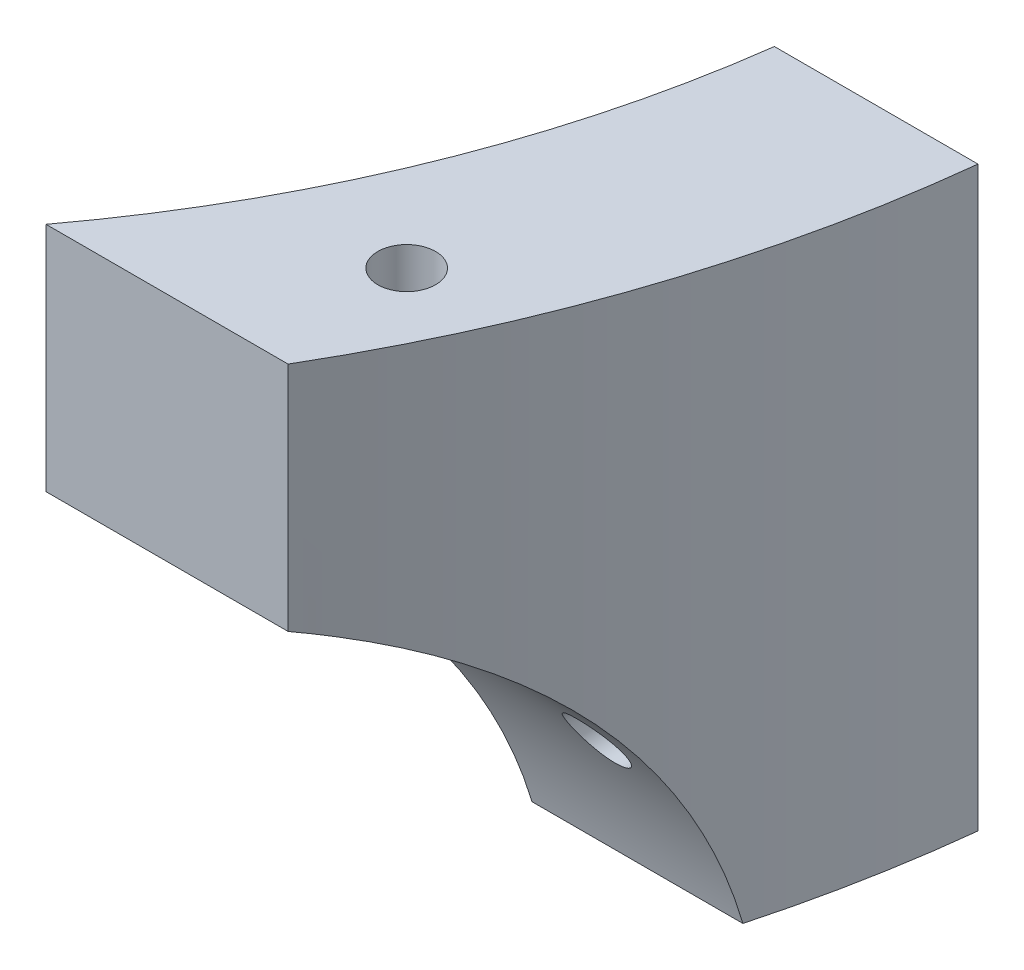
SolidWorks part; units mm, degrees
material "1023 Carbon Steel Sheet (SS)"
ref_plane "Front Plane" through (0, 0, 0) normal (0, 0, 1) x (1, 0, 0)
ref_plane "Top Plane" through (0, 0, 0) normal (0, 1, 0) x (1, 0, 0)
ref_plane "Right Plane" through (0, 0, 0) normal (1, 0, 0) x (0, 0, -1)
sketch "Sketch1" plane through (0, 0, 0) normal (0, 1, 0) x (1, 0, 0)
  line L0 (-1000, 0) -> (-104.805, 0) construction
  line L1 (0, -1000) -> (0, 49000) construction
  line L2 (91.805, -10) -> (90.2527, -10)
  line L3 (-76.805, 0) -> (76.805, 0)
  line L7 (-91.805, -10) -> (-90.2527, -10)
  line L9 (104.805, 0) -> (49000, 0) construction
  line L10 (-76.805, 0) -> (-76.805, 20)
  line L12 (-76.805, 0) -> (76.805, 0) construction
  line L13 (91.805, 20) -> (91.805, -10)
  line L14 (76.805, 20) -> (91.805, 20)
  line L17 (-76.805, 20) -> (-91.805, 20)
  line L18 (76.805, 0) -> (76.805, 20)
  line L19 (-91.805, 20) -> (-91.805, -10)
  arc A0 (-90.2527, -10) -> (90.2527, -10) centre (0, 0) ccw
  arc A1 (-76.805, 0) -> (76.805, 0) centre (0, 0) ccw
  dimension "D1" = 181.61
  dimension "D2" = 14
  dimension "D3" = 30
  dimension "D4" = 15
extrude "Boss-Extrude1" add sketch "Sketch1" against normal blind 60
sketch "Sketch25" plane through (0, -60, 0) normal (0, -1, 0) x (-1, 0, 0)
  line L0 (76.805, 20) -> (91.805, -10)
  line L1 (91.805, -10) -> (76.805, -10)
  line L2 (76.805, -10) -> (91.805, 20)
  line L3 (-91.805, -10) -> (-76.805, 20)
  line L4 (81.555, -3.5) -> (87.055, -3.5)
  line L5 (81.555, -3.5) -> (81.555, 13.5)
  line L6 (81.555, 13.5) -> (87.055, 13.5)
  line L7 (87.055, -3.5) -> (87.055, 13.5)
  line L8 (81.555, -3.5) -> (87.055, 13.5) construction
  line L9 (81.555, 13.5) -> (87.055, -3.5) construction
  line L10 (-76.805, 20) -> (-77.8097, -10)
  line L11 (-77.8097, -10) -> (-91.805, -10)
  line L12 (-77.8097, -10) -> (-91.805, 20)
  line L14 (-87.055, -3.5) -> (-81.555, -3.5)
  line L15 (-87.055, -3.5) -> (-87.055, 13.5)
  line L16 (-87.055, 13.5) -> (-81.555, 13.5)
  line L17 (-81.555, -3.5) -> (-81.555, 13.5)
  line L18 (-87.055, -3.5) -> (-81.555, 13.5) construction
  line L19 (-87.055, 13.5) -> (-81.555, -3.5) construction
  point P4 (84.305, 5)
  point P16 (-84.305, 5)
  dimension "D1" = 5.5
  dimension "D2" = 17
  dimension "D3" = 17
  dimension "D4" = 5.5
extrude "Boss-Extrude3" add sketch "Sketch25" along normal blind 20 contours L15 L16 L17 L14 | L5 L6 L7 L4
ref_plane "Plane4" through (0, 0, 90) normal (0, 0, 1) x (1, 0, 0)
fillet "Fillet1" radius 2.3 8 edges at (84.305, -60, 3.5) (81.555, -60, -5) (84.305, -60, -13.5) (87.055, -60, -5) (-87.055, -60, -5) (-84.305, -60, -13.5) (-84.305, -60, 3.5) (-81.555, -60, -5)
sketch "Sketch28" plane through (91.805, 0, 0) normal (1, 0, 0) x (0, 0, -1)
  line L2 (20, 0) -> (20, -60)
  line L3 (20, -60) -> (-10, -60)
  line L4 (-10, 0) -> (-10, -60)
  line L5 (9, -37) -> (1, -37)
  line L6 (9, -37) -> (9, -47)
  line L7 (9, -47) -> (1, -47)
  line L8 (1, -37) -> (1, -47)
  line L9 (9, -37) -> (1, -47) construction
  line L10 (9, -47) -> (1, -37) construction
  point P7 (5, -42)
  dimension "D1" = 11
  dimension "D2" = 8
  dimension "D3" = 10
  dimension "D4" = 13
extrude "Cut-Extrude17" cut sketch "Sketch28" against normal blind 265 contours L5 L8 L7 L6
sketch "Sketch30" plane through (0, 0, -20) normal (0, 0, -1) x (-1, 0, 0)
  line L0 (-91.805, -60) -> (-91.805, 0) construction
  line L1 (91.805, 0) -> (-91.805, 0)
  line L2 (91.805, 0) -> (91.805, -30)
  line L3 (91.805, -30) -> (-91.805, -30)
  line L4 (-91.805, 0) -> (-91.805, -30)
  dimension "D1" = 30
extrude "Cut-Extrude19" cut sketch "Sketch30" against normal through all both and the other way through all
sketch "Sketch32" plane through (0, 0, -20) normal (0, 0, -1) x (-1, 0, 0)
  line L0 (-91.805, -60) -> (-91.805, -30) construction
  line L1 (-82.805, -39) -> (-85.805, -39)
  line L2 (-82.805, -39) -> (-82.805, -53)
  line L3 (-82.805, -53) -> (-85.805, -53)
  line L4 (-85.805, -39) -> (-85.805, -53)
  line L8 (-76.805, -30) -> (-91.805, -30) construction
  line L9 (0, 0) -> (0, -102.7115)
  line L10 (53.2739, -37) -> (53.2739, -51)
  line L11 (-66.6352, -37) -> (-63.6352, -37)
  line L12 (-66.6352, -37) -> (-66.6352, -51)
  line L13 (-66.6352, -51) -> (-63.6352, -51)
  line L14 (-63.6352, -37) -> (-63.6352, -51)
  line L15 (-50.2739, -37) -> (-53.2739, -37)
  line L16 (-50.2739, -37) -> (-50.2739, -51)
  line L17 (-50.2739, -51) -> (-53.2739, -51)
  line L18 (-53.2739, -37) -> (-53.2739, -51)
  line L19 (50.2739, -51) -> (53.2739, -51)
  line L20 (50.2739, -37) -> (50.2739, -51)
  line L21 (50.2739, -37) -> (53.2739, -37)
  line L22 (63.6352, -37) -> (63.6352, -51)
  line L23 (66.6352, -51) -> (63.6352, -51)
  line L24 (66.6352, -37) -> (66.6352, -51)
  line L25 (66.6352, -37) -> (63.6352, -37)
  line L26 (85.805, -39) -> (85.805, -53)
  line L27 (82.805, -53) -> (85.805, -53)
  line L28 (82.805, -39) -> (82.805, -53)
  line L29 (82.805, -39) -> (85.805, -39)
  point P19 (-51.7739, -37)
  point P20 (-65.1352, -37)
  dimension "D1" = 3
  dimension "D2" = 6
  dimension "D3" = 14
  dimension "D4" = 9
  dimension "D5" = 1.5
  dimension "D6" = 1.5
extrude "Cut-Extrude20" cut sketch "Sketch32" against normal through all both and the other way through all contours L14 L11 L12 L13 | L15 L18 L17 L16 | L4 L3 L2 L1 | L24 L23 L22 L25 | L10 L19 L20 L21 | L28 L27 L26 L29
sketch "Sketch33" plane through (0, -60, 0) normal (0, -1, 0) x (-1, 0, 0)
  line L0 (90.2527, -10) -> (76.1512, -10)
  line L1 (0, 0) -> (0, -98.2692)
  line L2 (73.8985, -52.7689) -> (61.5906, -45.8869)
  line L3 (-90.2527, -10) -> (-76.1512, -10)
  line L4 (-73.8985, -52.7689) -> (-61.5906, -45.8869)
  arc A0 (-76.805, 0) -> (76.805, 0) centre (0, 0) ccw construction
  arc A1 (76.1512, -10) -> (61.5906, -45.8869) centre (0, 0) cw
  arc A2 (90.2527, -10) -> (73.8985, -52.7689) centre (0, 0) cw
  arc A3 (-90.2527, -10) -> (90.2527, -10) centre (0, 0) ccw construction
  arc A4 (-76.1512, -10) -> (-61.5906, -45.8869) centre (0, 0) ccw
  arc A5 (-90.2527, -10) -> (-73.8985, -52.7689) centre (0, 0) ccw
  arc M9 (76.805, 0) -> (-76.805, 0) centre (0, 0) cw
  arc M14 (-90.2527, -10) -> (90.2527, -10) centre (0, 0) ccw
extrude "Boss-Extrude4" add sketch "Sketch33" along normal blind 40 contours L4 L3 M14 M9 | L2 L0 M14 M9
sketch "Sketch37" plane through (0, 0, 0) normal (1, 0, 0) x (0, 0, -1)
  line L0 (-0.8813, -100) -> (-23.6906, -100)
  line L1 (-45.8869, -59.9172) -> (-45.8869, -76.0376)
  line L2 (-45.8869, -59.9172) -> (-66.9482, -59.9172)
  line L3 (-66.9482, -59.9172) -> (-63.7464, -92.4419)
  line L4 (-63.7464, -92.4419) -> (-47.5718, -115.3465)
  line L5 (-47.5718, -115.3465) -> (-8.0864, -115.3465)
  line L6 (-8.0864, -115.3465) -> (-0.8813, -100)
  line L7 (-45.8869, -100) -> (-10, -100) construction
  line L8 (-45.8869, -100) -> (-45.8869, -60) construction
  arc A0 (-23.6906, -100) -> (-45.8869, -76.0376) centre (-56.36, -108.0002) ccw
extrude "Cut-Extrude21" cut sketch "Sketch37" against normal through all both and the other way through all contours L6 L0 A0 L1 L2 L3 L4 L5
sketch "Sketch38" plane through (0, 0, 0) normal (1, 0, 0) x (0, 0, -1)
  line L0 (-90.805, -60) -> (-66.9401, -60) construction
  line L1 (20, -30) -> (-90.805, -30)
  line L2 (20, -30) -> (20, -60)
  line L3 (-10, -60) -> (-90.805, -60)
  line L4 (-90.805, -30) -> (-90.805, -60)
  line L5 (-90.805, -30) -> (-90.805, -60) construction
  line L6 (-10, -100) -> (-10, -60) construction
  line L8 (20, -60) -> (20, -100)
  line L9 (20, -100) -> (-10, -100)
  line L10 (-10, -60) -> (-10, -100)
extrude "Cut-Extrude22" cut sketch "Sketch38" against normal through all both and the other way through all
sketch "Sketch40" plane through (0, -100, 0) normal (0, -1, 0) x (-1, 0, 0)
  line L1 (90.2527, -10) -> (58.4518, -10)
  line L2 (90.2527, -10) -> (90.2527, -69.8018)
  line L3 (90.2527, -69.8018) -> (58.4518, -69.8018)
  line L4 (58.4518, -10) -> (58.4518, -69.8018)
extrude "Cut-Extrude23" cut sketch "Sketch40" against normal blind 55
sketch "Sketch41" plane through (0, 0, 10) normal (0, 0, -1) x (-1, 0, 0)
  circle A0 centre (-82.2527, -89.36) radius 2
  dimension "D2" = 4
  dimension "D1" = 8
extrude "Cut-Extrude24" cut sketch "Sketch41" against normal blind 55 contours A0
sketch "Sketch42" plane through (0, -60, 0) normal (0, 1, 0) x (1, 0, 0)
  circle A0 centre (76.7086, -36.0238) radius 2
  dimension "D1" = 4
  dimension "D2" = 10
extrude "Cut-Extrude25" cut sketch "Sketch42" against normal blind 55
